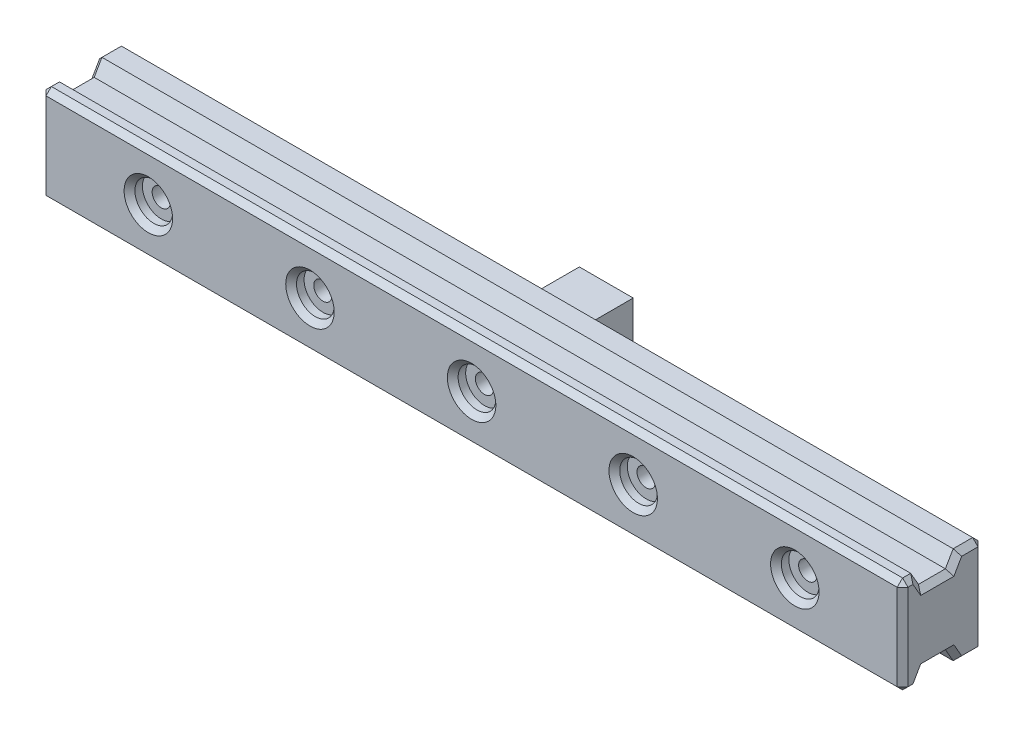
SolidWorks part; units mm, degrees
material "1060 Alloy"
ref_plane "Front Plane" through (0, 0, 0) normal (0, 0, 1) x (1, 0, 0)
ref_plane "Top Plane" through (0, 0, 0) normal (0, 1, 0) x (1, 0, 0)
ref_plane "Right Plane" through (0, 0, 0) normal (1, 0, 0) x (0, 0, -1)
sketch "Sketch1" plane through (0, 0, 0) normal (0, 0, 1) x (1, 0, 0)
  line L1 (-80, -9) -> (80, -9)
  line L2 (-80, -9) -> (-80, 9)
  line L3 (-80, 9) -> (80, 9)
  line L4 (80, -9) -> (80, 9)
  line L5 (-80, -9) -> (80, 9) construction
  line L6 (-80, 9) -> (80, -9) construction
  point P0 (0, 0)
  dimension "D1" = 160
  dimension "D2" = 18
extrude "Boss-Extrude1" add sketch "Sketch1" along normal blind 15
sketch "Sketch2" plane through (80, 0, 0) normal (1, 0, 0) x (0, 0, -1)
  line L0 (-12.5, 9) -> (-4.6132, 9)
  line L1 (-15, 9) -> (0, 9) construction
  line L2 (-4.6132, 9) -> (-6.0566, 6.5)
  line L3 (-6.0566, 6.5) -> (-11.0566, 6.5)
  line L4 (-11.0566, 6.5) -> (-12.5, 9)
  line L5 (0, 0) -> (-15, 0) construction
  line L6 (0, -9) -> (0, 9) construction
  line L7 (-15, -9) -> (-15, 9) construction
  line L8 (-11.0566, -6.5) -> (-12.5, -9)
  line L9 (-6.0566, -6.5) -> (-11.0566, -6.5)
  line L10 (-4.6132, -9) -> (-6.0566, -6.5)
  line L11 (-12.5, -9) -> (-4.6132, -9)
  dimension "D1" = 2.5
  dimension "D2" = 2.5
  dimension "D3" = 60
  dimension "D4" = 5
extrude "Cut-Extrude1" cut sketch "Sketch2" against normal through all
sketch "Sketch3" plane through (0, 0, 0) normal (0, 0, -1) x (-1, 0, 0)
  line L1 (-5, -5) -> (5, -5)
  line L2 (-5, -5) -> (-5, 5)
  line L3 (-5, 5) -> (5, 5)
  line L4 (5, -5) -> (5, 5)
  line L5 (-5, -5) -> (5, 5) construction
  line L6 (-5, 5) -> (5, -5) construction
  point P0 (0, 0)
  dimension "D1" = 10
  dimension "D2" = 10
extrude "Boss-Extrude2" add sketch "Sketch3" along normal blind 10
hole_wizard "CBORE for M3 Pan Head Screw1" positions "3DSketch1" profile "Sketch4" counterbore size "M3" standard "ISO"
sketch3d "3DSketch1"
  point P0 (0, 0, 15)
sketch "Sketch4" plane through (0, 0, 15) normal (1, 0, 0) x (0, -1, 0)
  line L0 (0, 0) -> (0, 15.001)
  line L1 (0, 15.001) -> (1.7, 15.001)
  line L3 (1.7, 15.001) -> (1.7, 2.4)
  line L4 (1.7, 2.4) -> (3.5, 2.4)
  line L5 (3.5, 2.4) -> (3.5, 0)
  line L7 (3.5, 0) -> (0, 0)
  line L11 (0, -6.35) -> (0, 107.95) construction
  dimension "Thru Hole Dia." = 3.4
  dimension "Thru Hole Depth" = 15.001
  dimension "C'Bore Dia." = 7
  dimension "C'Bore Depth" = 2.4
chamfer "Chamfer1" distance 1 angle 45 29 edges at (3.5, 0, 15) (80, 7.75, 5.3349) (80, 9, 2.3066) (80, 0, 0) (80, -9, 2.3066) (80, -7.75, 5.3349) (80, -6.5, 8.5566) (80, -7.75, 11.7783) (80, -9, 13.75) (80, 0, 15) (80, 6.5, 8.5566) (80, 7.75, 11.7783) (80, 9, 13.75) (-80, 0, 15) (0, -9, 15) (-80, -9, 13.75) (-80, -7.75, 11.7783) (-80, -6.5, 8.5566) (-80, -7.75, 5.3349) (-80, -9, 2.3066) (0, -9, 0) (-80, 0, 0) (0, 9, 0) (-80, 9, 2.3066) (-80, 7.75, 5.3349) (-80, 6.5, 8.5566) (-80, 7.75, 11.7783) (-80, 9, 13.75) (0, 9, 15)
pattern_linear "LPattern2" count 3 spacing 30 along (1, 0, 0) of "CBORE for M3 Pan Head Screw1"
pattern_linear "LPattern3" count 3 spacing 30 along (-1, 0, 0) of "CBORE for M3 Pan Head Screw1"
chamfer "Chamfer2" distance 1 angle 45 4 edges at (63.5, 0, 15) (33.5, 0, 15) (-26.5, 0, 15) (-56.5, 0, 15)
